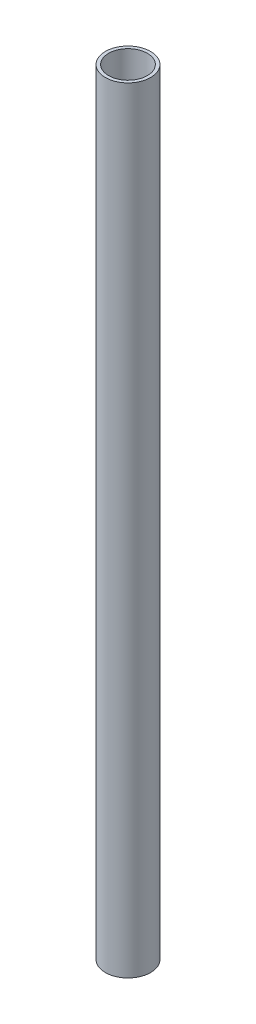
SolidWorks part; units mm, degrees
ref_plane "Front Plane" through (0, 0, 0) normal (0, 0, 1) x (1, 0, 0)
ref_plane "Top Plane" through (0, 0, 0) normal (0, 1, 0) x (1, 0, 0)
ref_plane "Right Plane" through (0, 0, 0) normal (1, 0, 0) x (0, 0, -1)
sketch "Sketch1" plane through (0, 0, 0) normal (0, 1, 0) x (1, 0, 0)
  circle A0 centre (0, 0) radius 3.5
  circle A1 centre (0, 0) radius 3
  dimension "D1" = 6
  dimension "D2" = 7
extrude "Boss-Extrude1" add sketch "Sketch1" along normal mid plane 120
